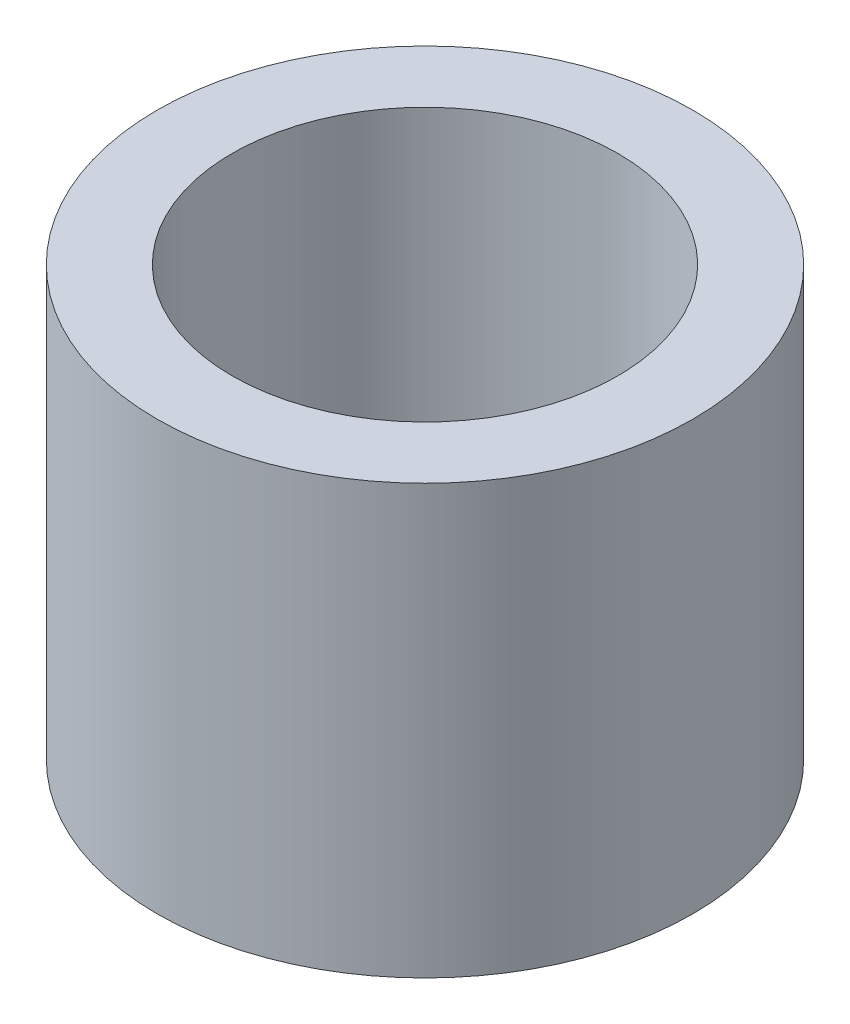
SolidWorks part; units mm, degrees
material "2.1020 (CuSn6)"
ref_plane "Front Plane" through (0, 0, 0) normal (0, 0, 1) x (1, 0, 0)
ref_plane "Top Plane" through (0, 0, 0) normal (0, 1, 0) x (1, 0, 0)
ref_plane "Right Plane" through (0, 0, 0) normal (1, 0, 0) x (0, 0, -1)
sketch "Sketch1" plane through (0, 0, 0) normal (0, 1, 0) x (1, 0, 0)
  circle A0 centre (0, 0) radius 3.175
extrude "Boss-Extrude1" add sketch "Sketch1" along normal blind 5.08
sketch "Sketch3" plane through (0, 0, 0) normal (0, -1, 0) x (1, 0, 0)
  circle A0 centre (0, 0) radius 2.286
extrude "Cut-Extrude1" cut sketch "Sketch3" against normal blind 5.08
